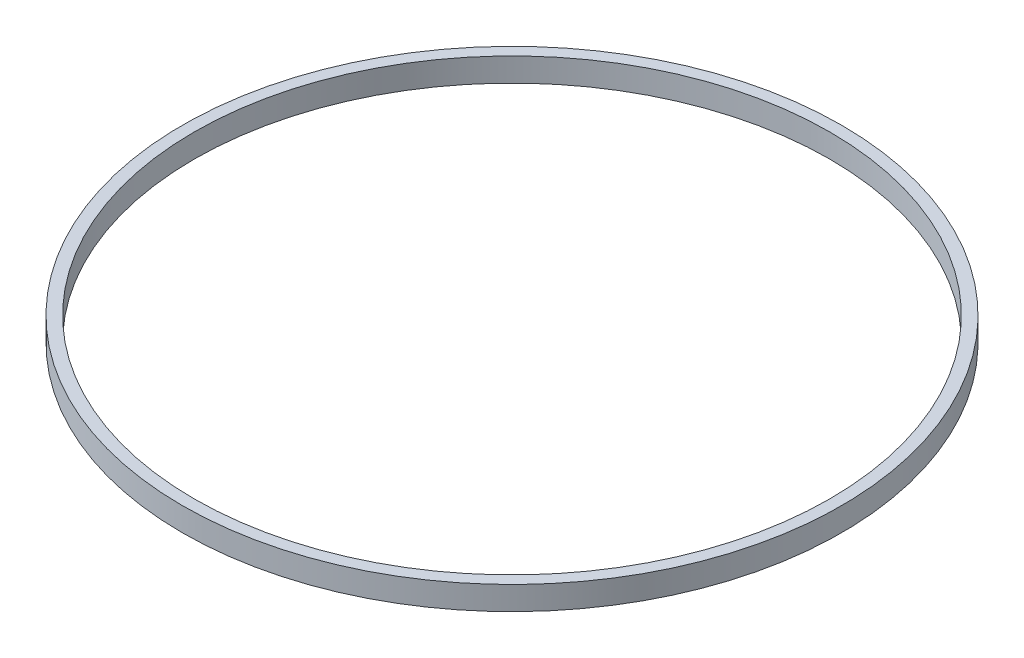
SolidWorks part; units mm, degrees
ref_plane "Front Plane" through (0, 0, 0) normal (0, 0, 1) x (1, 0, 0)
ref_plane "Top Plane" through (0, 0, 0) normal (0, 1, 0) x (1, 0, 0)
ref_plane "Right Plane" through (0, 0, 0) normal (1, 0, 0) x (0, 0, -1)
sketch "Sketch1" plane through (0, 0, 0) normal (0, 1, 0) x (1, 0, 0)
  circle A0 centre (0, 0) radius 70
  circle A1 centre (0, 0) radius 67.5
  dimension "D1" = 140
extrude "Boss-Extrude1" add sketch "Sketch1" along normal mid plane 5
